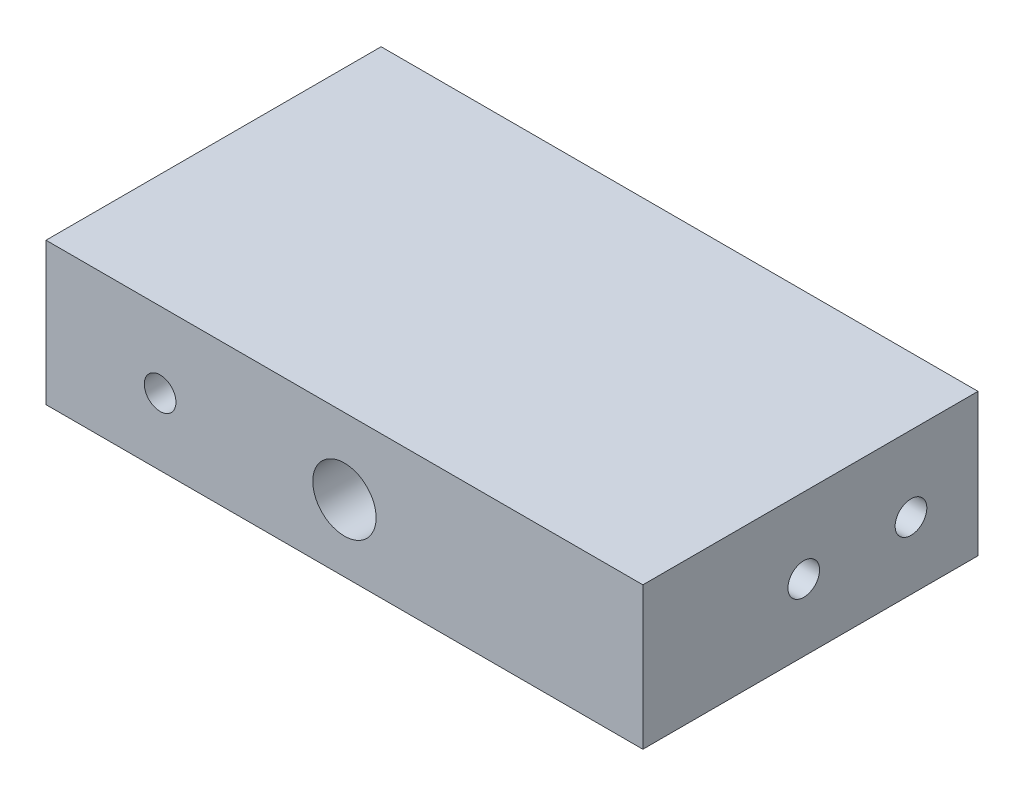
SolidWorks part; units mm, degrees
material "ABS"
ref_plane "X-Y Datum" through (0, 0, 0) normal (0, 0, 1) x (1, 0, 0)
ref_plane "X-Z Datum" through (0, 0, 0) normal (0, 1, 0) x (1, 0, 0)
ref_plane "Y-Z Datum" through (0, 0, 0) normal (1, 0, 0) x (0, 0, -1)
sketch "Sketch1" plane through (0, 0, 0) normal (0, 0, 1) x (1, 0, 0)
  line L1 (-28.275, 6.35) -> (28.275, 6.35)
  line L2 (-28.275, 6.35) -> (-28.275, -6.35)
  line L3 (-28.275, -6.35) -> (28.275, -6.35)
  line L4 (28.275, 6.35) -> (28.275, -6.35)
  line L5 (-28.275, 6.35) -> (28.275, -6.35) construction
  line L6 (-28.275, -6.35) -> (28.275, 6.35) construction
  point P0 (0, 0)
  dimension "D1" = 56.55
  dimension "D2" = 12.7
extrude "Boss-Extrude1" add sketch "Sketch1" along normal blind 31.75 contours L2 L3 L4 L1
sketch "Sketch2" plane through (0, 0, 31.75) normal (0, 0, 1) x (1, 0, 0)
  line L0 (-28.275, 0) -> (28.275, 0) construction
  line L1 (-28.275, 6.35) -> (-28.275, -6.35) construction
  line L2 (28.275, 6.35) -> (28.275, -6.35) construction
  line L3 (-17.4625, 0) -> (17.4625, 0) construction
  circle A0 centre (17.4625, 0) radius 1.5 construction
  circle A1 centre (-17.4625, 0) radius 1.5
  circle A2 centre (0, 0) radius 3
  point P10 (0, 0)
  dimension "D1" = 3
  dimension "D3" = 6
  dimension "D2" = 34.925
extrude "Cut-Extrude1" cut sketch "Sketch2" against normal blind 10 contours A1 L0 L3 | L0 A1 L3 | L0 L3 A0 | L3 L0 A0 | A2
sketch "Sketch3" plane through (-28.275, 0, 0) normal (-1, 0, 0) x (0, 0, 1)
  line L0 (31.75, 0) -> (0, 0) construction
  line L1 (31.75, 6.35) -> (31.75, -6.35) construction
  line L2 (0, 6.35) -> (0, -6.35) construction
  circle A0 centre (6.35, 0) radius 1.5
  circle A1 centre (16.51, 0) radius 1.5
  dimension "D1" = 3
  dimension "D2" = 10.16
  dimension "D3" = 6.35
extrude "Cut-Extrude2" cut sketch "Sketch3" against normal blind 8 contours A0 L0 | L0 A0 | A1 L0 | L0 A1
sketch "Sketch4" plane through (0, 6.35, 0) normal (0, 1, 0) x (1, 0, 0)
  line L4 (28.275, 0) -> (-28.275, 0)
  line L5 (-28.275, 0) -> (-28.275, -31.75)
  line L6 (-28.275, -31.75) -> (28.275, -31.75)
  line L7 (28.275, -31.75) -> (28.275, 0)
  line L8 (28.275, 0) -> (-28.275, 0)
  line L9 (-28.275, 0) -> (-28.275, -31.75)
  line L10 (-28.275, -31.75) -> (28.275, -31.75)
  line L11 (28.275, -31.75) -> (28.275, 0)
  dimension "D1" = 0
extrude "Boss-Extrude2" add sketch "Sketch4" along normal blind 0.7937
mirror "Mirror1" about plane through (0, 0, 0) normal (1, 0, 0) of "Cut-Extrude2"
